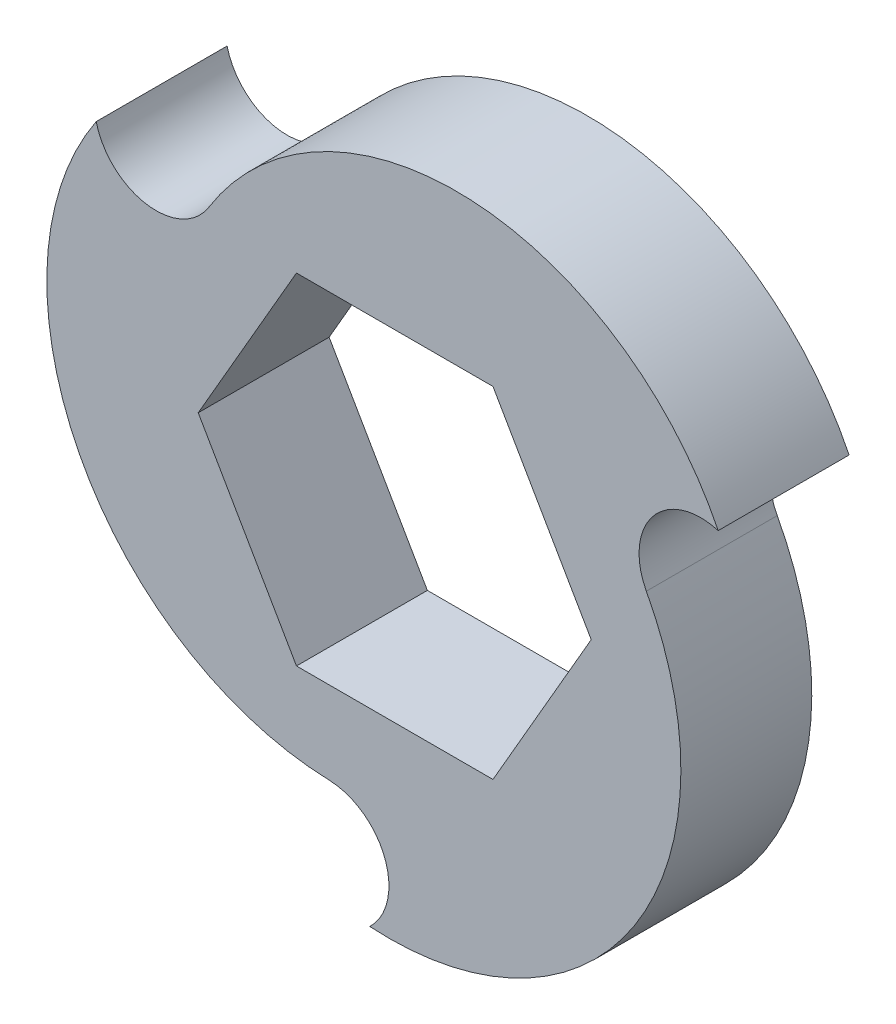
SolidWorks part; units mm, degrees
ref_plane "Front Plane" through (0, 0, 0) normal (0, 0, 1) x (1, 0, 0)
ref_plane "Top Plane" through (0, 0, 0) normal (0, 1, 0) x (1, 0, 0)
ref_plane "Right Plane" through (0, 0, 0) normal (1, 0, 0) x (0, 0, -1)
sketch "Sketch1" plane through (0, 0, 0) normal (0, 0, 1) x (1, 0, 0)
  line L6 (0, 0) -> (66.1503, 0) construction
  line L7 (7.5056, 0) -> (3.7528, 6.5)
  line L8 (3.7528, 6.5) -> (-3.7528, 6.5)
  line L9 (-3.7528, 6.5) -> (-7.5056, 0)
  line L10 (-7.5056, 0) -> (-3.7528, -6.5)
  line L11 (-3.7528, -6.5) -> (3.7528, -6.5)
  line L12 (3.7528, -6.5) -> (7.5056, 0)
  line L13 (0, 0) -> (-15.3926, 15.1529) construction
  line L14 (0, 0) -> (21.3672, 5.9055) construction
  circle A0 centre (0, 0) radius 13.75 construction
  arc A1 (271.8524, 134.8606) -> (128.8311, 107.2295) centre (210.3708, 69.1338) ccw construction
  arc A2 (101.7797, 101.1876) -> (128.8311, 107.2295) centre (112.9762, 114.637) ccw construction
  arc A3 (271.8524, 134.8606) -> (263.5592, 108.4124) centre (277.9018, 118.4394) ccw construction
  arc A4 (215.9777, -29.2632) -> (197.2195, -8.857) centre (198.7319, -26.2915) ccw construction
  arc A5 (215.9777, -29.2632) -> (263.5592, 108.4124) centre (189.7975, 56.8448) ccw construction
  arc A6 (101.7797, 101.1876) -> (197.2195, -8.857) centre (189.4416, 80.8063) ccw construction
  circle A7 centre (0, 0) radius 6.5 construction
  arc A8 (-7.1061, 6.9954) -> (12.3558, 6.033) centre (2.3581, 1.1198) cw
  arc A9 (12.3558, 6.033) -> (9.6113, 2.6564) centre (11.6908, 3.7698) ccw
  arc A10 (9.6113, 2.6564) -> (-0.9532, -13.7169) centre (-0.2093, -2.602) cw
  arc A11 (-0.9532, -13.7169) -> (-2.5052, -9.6518) centre (-2.5806, -12.0094) ccw
  arc A12 (-2.5052, -9.6518) -> (-11.4026, 7.6839) centre (-2.1488, 1.4823) cw
  arc A13 (-11.4026, 7.6839) -> (-7.1061, 6.9954) centre (-9.1102, 8.2396) ccw
  point P9 (95.6823, 117.3148)
  point P11 (128.6223, 31.4883)
  point P12 (212.2895, -27.5921)
  dimension "D1" = 27.5
  dimension "D2" = 120
  dimension "D3" = 13
  dimension "D4" = 3
extrude "Boss-Extrude1" add sketch "Sketch1" along normal blind 5
